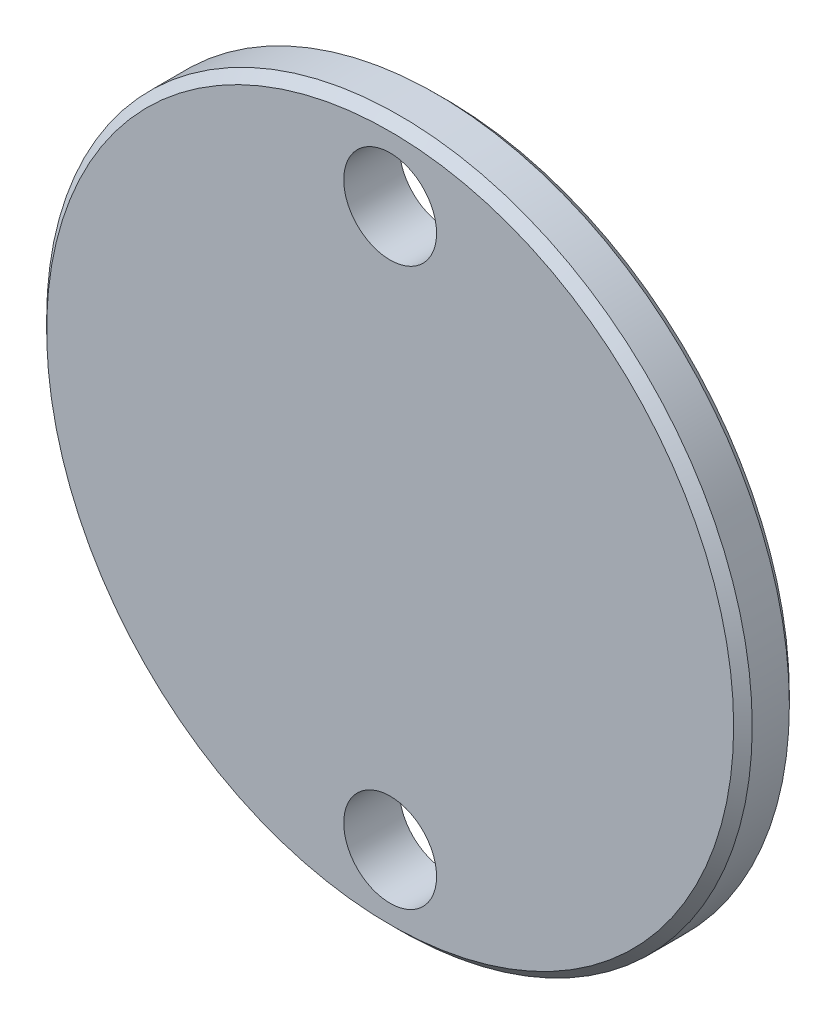
SolidWorks part; units mm, degrees
ref_plane "前视基准面" through (0, 0, 0) normal (0, 0, 1) x (1, 0, 0)
ref_plane "上视基准面" through (0, 0, 0) normal (0, 1, 0) x (1, 0, 0)
ref_plane "右视基准面" through (0, 0, 0) normal (1, 0, 0) x (0, 0, -1)
sketch "草图1" plane through (0, 0, 0) normal (0, 0, 1) x (1, 0, 0)
  circle A0 centre (0, 0) radius 19
extrude "拉伸1" add sketch "草图1" along normal blind 3
sketch "草图2" plane through (0, 0, 3) normal (0, 0, 1) x (1, 0, 0)
  circle A0 centre (0, 15) radius 2.5
  circle A1 centre (0, -15) radius 2.5
  dimension "D1" = 5
  dimension "D2" = 15
extrude "切除-拉伸1" cut sketch "草图2" against normal blind 13
chamfer "倒角1" distance 0.5 angle 45 2 edges at (19, 0, 0) (19, 0, 3)
